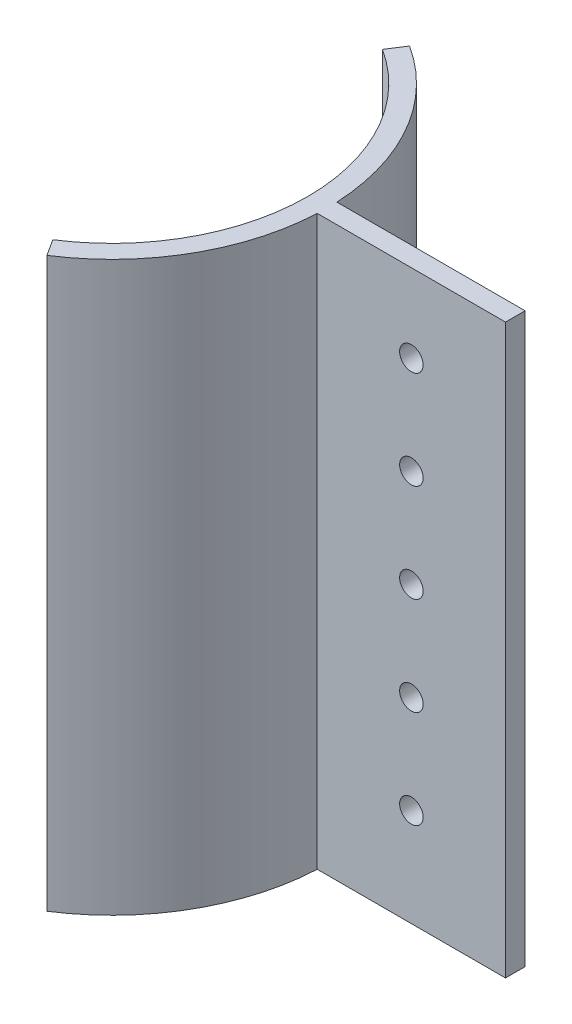
SolidWorks part; units mm, degrees
other "Connection Feature"
ref_plane "Front Plane" through (0, 0, 0) normal (0, 0, 1) x (1, 0, 0)
ref_plane "Top Plane" through (0, 0, 0) normal (0, 1, 0) x (1, 0, 0)
ref_plane "Right Plane" through (0, 0, 0) normal (1, 0, 0) x (0, 0, -1)
sketch "Sketch1" plane through (0, 0, 0) normal (0, 1, 0) x (1, 0, 0)
  line L0 (0, 0) -> (13.5076, -21.0368) construction
  line L1 (0, 0) -> (13.5076, 21.0368) construction
  line L2 (0, 0) -> (25, 0) construction
  circle A0 centre (0, 0) radius 25 construction
  arc A1 (13.5076, 21.0368) -> (13.5076, -21.0368) centre (0, 0) cw
  dimension "D1" = 50
  dimension "D2" = 50
extrude "Extrude-Thin1" add sketch "Sketch1" along normal mid plane 72.5 thin thin type one direction reverse wall 2.5
sketch "Sketch2" plane through (0, 0, 0) normal (0, 0, 1) x (1, 0, 0)
  line L0 (27.5, 36.25) -> (14.8583, 36.25) construction
  line L1 (26.5, 36.25) -> (51.5, 36.25)
  line L2 (26.5, 36.25) -> (26.5, -36.25)
  line L3 (26.5, -36.25) -> (51.5, -36.25)
  line L4 (51.5, 36.25) -> (51.5, -36.25)
  line L5 (14.8583, -36.25) -> (27.5, -36.25) construction
  line L6 (25, -36.25) -> (25, 36.25) construction
  dimension "D1" = 1.5
  dimension "D2" = 25
extrude "Boss-Extrude1" add sketch "Sketch2" along normal mid plane 2.5 contours L4 L3 L2 L1
hole_wizard "Ø3.0mm Dowel Hole1" positions "Sketch3" profile "Sketch4" hole size "Ø3.0" standard "ANSI Metric" end condition through all
sketch "Sketch3" plane through (0, 0, 1.25) normal (0, 0, 1) x (1, 0, 0)
  line L0 (39.4858, 36.25) -> (39.4858, -36.25) construction
  line L1 (27.4716, 36.25) -> (51.5, 36.25) construction
  line L2 (27.4716, -36.25) -> (51.5, -36.25) construction
  point P0 (39.4858, 26.25)
  dimension "D1" = 10
sketch "Sketch4" plane through (39.4858, 26.25, 1.25) normal (1, 0, 0) x (0, -1, 0)
  line L0 (0, 0) -> (0, 2.5)
  line L1 (0, 2.5) -> (1.525, 2.5)
  line L2 (1.5, 2.475) -> (1.5, 0)
  line L5 (1.5, 0) -> (0, 0)
  line L7 (1.525, 2.5) -> (1.5, 2.475)
  line L8 (-1.525, 2.5) -> (-1.5, 2.475) construction
  line L11 (0, -6.35) -> (0, 107.95) construction
  dimension "Thru Hole Dia." = 3
  dimension "Thru Hole Depth" = 2.5
  dimension "Far C'Sink Dia." = 3.05
  dimension "Far C'Sink Angle" = 90
pattern_linear "LPattern1" count 5 spacing 12.5 along (0, -1, 0) of "Ø3.0mm Dowel Hole1"
other "Configuration Table"
